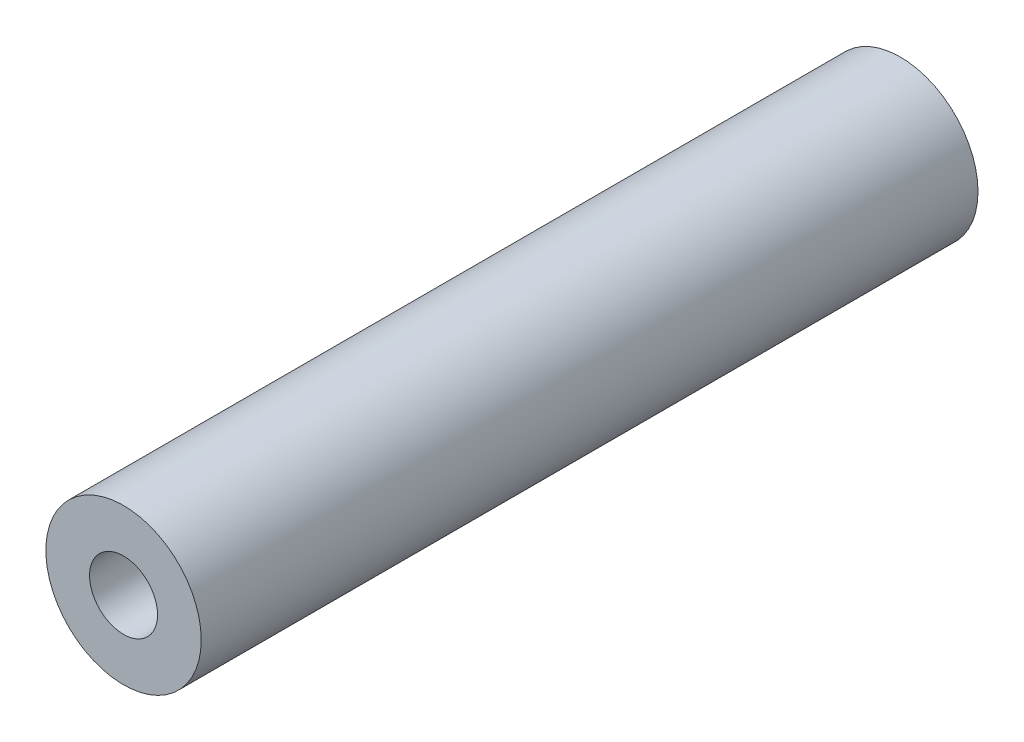
SolidWorks part; units mm, degrees
ref_plane "Спереди" through (0, 0, 0) normal (0, 0, 1) x (1, 0, 0)
ref_plane "Сверху" through (0, 0, 0) normal (0, 1, 0) x (1, 0, 0)
ref_plane "Справа" through (0, 0, 0) normal (1, 0, 0) x (0, 0, -1)
sketch "Эскиз1" plane through (0, 0, 0) normal (0, 0, 1) x (1, 0, 0)
  circle A0 centre (0, 0) radius 1.75
  circle A1 centre (0, 0) radius 4
  point P3 (0, 0)
  dimension "D1" = 3.5
  dimension "D2" = 2.25
extrude "Бобышка-Вытянуть1" add sketch "Эскиз1" along normal blind 40
